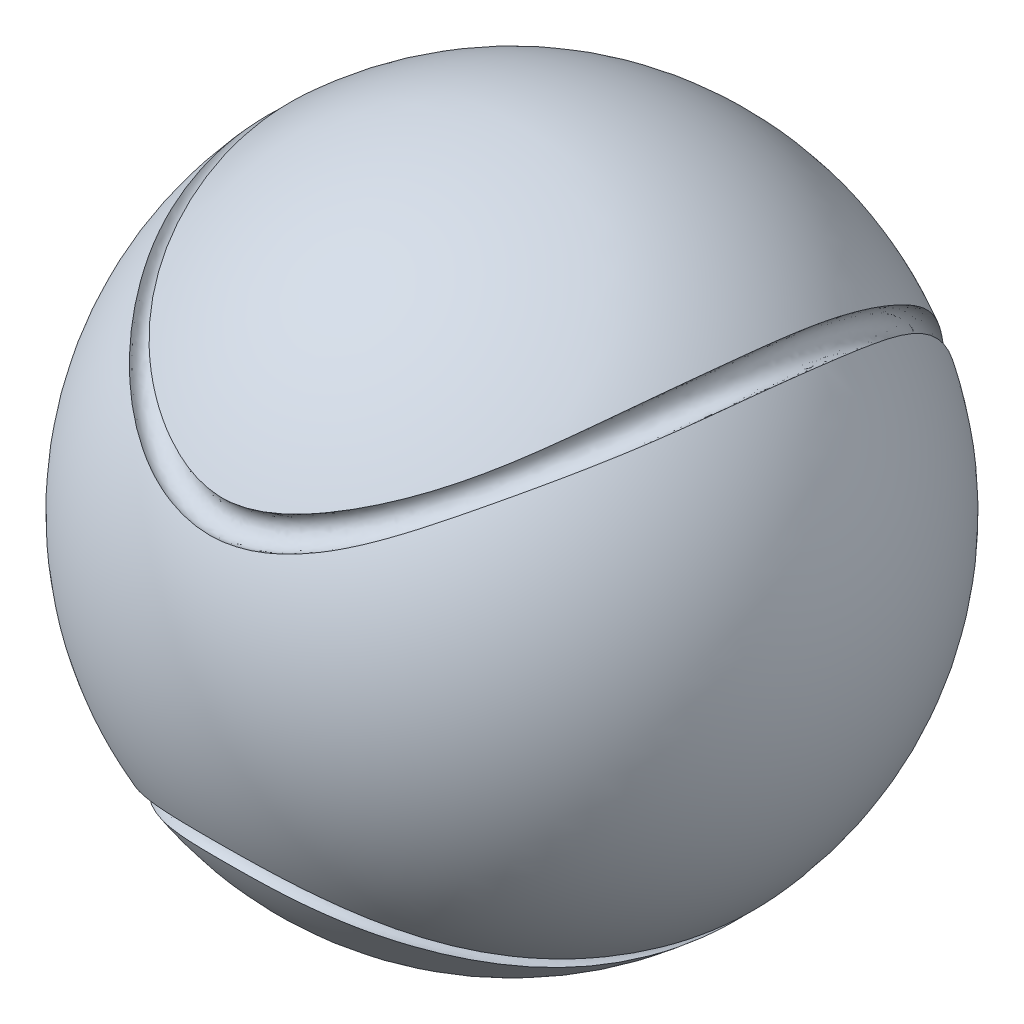
SolidWorks part; units mm, degrees
ref_plane "Front Plane" through (0, 0, 0) normal (0, 0, 1) x (1, 0, 0)
ref_plane "Top Plane" through (0, 0, 0) normal (0, 1, 0) x (1, 0, 0)
ref_plane "Right Plane" through (0, 0, 0) normal (1, 0, 0) x (0, 0, -1)
sketch "Sketch1" plane through (0, 0, 0) normal (0, 1, 0) x (1, 0, 0)
  line L0 (0, 40) -> (0, -40)
  arc A0 (0, 40) -> (0, -40) centre (0, 0) cw
  dimension "D1" = 40
revolve "Revolve-Thin3" add sketch "Sketch1" angle 360 about L0 wall 4
sketch "Sketch2" plane through (0, 0, 0) normal (0, 1, 0) x (1, 0, 0)
  line L0 (-17.5, 35.9687) -> (17.5, 35.9687) construction
  circle A0 centre (0, 0) radius 40 construction
  dimension "D1" = 35
sketch "Sketch3" plane through (0, 0, 0) normal (1, 0, 0) x (0, 0, -1)
  line L0 (-35.9687, 17.5) -> (-35.9687, -17.5) construction
  circle A0 centre (0, 0) radius 40 construction
  dimension "D1" = 35
sketch "Sketch4" plane through (0, 0, 0) normal (0, 0, 1) x (1, 0, 0)
  line L1 (28.2843, -28.2843) -> (-28.2843, -28.2843) construction
  line L2 (28.2843, -28.2843) -> (28.2843, 28.2843) construction
  line L3 (28.2843, 28.2843) -> (-28.2843, 28.2843) construction
  line L4 (-28.2843, -28.2843) -> (-28.2843, 28.2843) construction
  line L5 (28.2843, -28.2843) -> (-28.2843, 28.2843) construction
  line L6 (28.2843, 28.2843) -> (-28.2843, -28.2843) construction
  circle A0 centre (0, 0) radius 40 construction
  point P0 (0, 0)
sketch3d "3DSketch1"
  line L0 (28.2843, 28.2843, 0) -> (-28.2843, -28.2843, 0) construction
  line L1 (28.2843, -28.2843, 0) -> (28.2843, 28.2843, 0) construction
  line L2 (28.2843, -28.2843, 0) -> (-28.2843, 28.2843, 0) construction
  line L3 (28.2843, -28.2843, 0) -> (-28.2843, -28.2843, 0) construction
  spline S0 degree 3 poles (-40.9873, -40.9873, 0) (-5.7563, 0, -53.9531) (-40.9873, 40.9873, 0) (0, 5.7563, 53.9531) (40.9873, 40.9873, 0) (5.7563, 0, -53.9531) (40.9873, -40.9873, 0) (0, -5.7563, 53.9531) (-40.9873, -40.9873, 0) (-5.7563, 0, -53.9531) (-40.9873, 40.9873, 0) knots -0.375 -0.25 -0.125 0 0.125 0.25 0.375 0.5 0.625 0.75 0.875 1 1.125 1.25 1.375 only from (-17.5, 0, -35.9687) to (-17.5, 0, -35.9687)
sketch "Sketch5" plane through (0, 0, 0) normal (0, 1, 0) x (1, 0, 0)
  circle A0 centre (-17.5, 35.9687) radius 1.75
  dimension "D1" = 3.5
sweep "Cut-Sweep1" cut profiles "Sketch5" path "3DSketch1"
